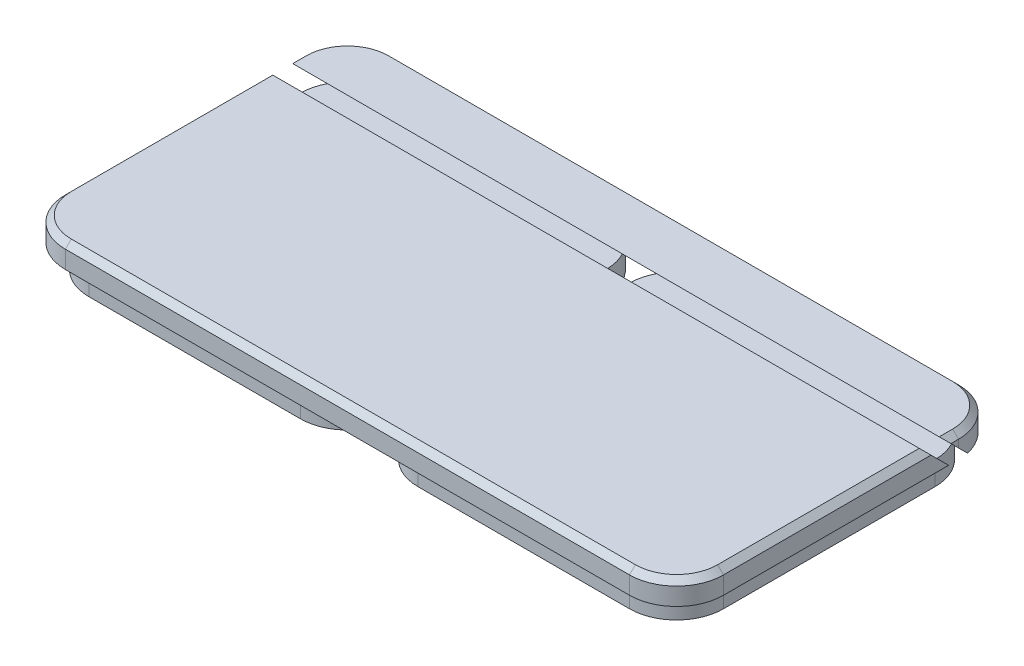
SolidWorks part; units mm, degrees
ref_plane "Front Plane" through (0, 0, 0) normal (0, 0, 1) x (1, 0, 0)
ref_plane "Top Plane" through (0, 0, 0) normal (0, 1, 0) x (1, 0, 0)
ref_plane "Right Plane" through (0, 0, 0) normal (1, 0, 0) x (0, 0, -1)
sketch "Sketch5" plane through (0, 0, 0) normal (0, 1, 0) x (1, 0, 0)
  line L1 (-22.5, -32.5) -> (22.5, -32.5)
  line L2 (-32.5, -22.5) -> (-32.5, 22.5)
  line L3 (-22.5, 32.5) -> (22.5, 32.5)
  line L4 (32.5, -22.5) -> (32.5, 22.5)
  line L5 (-32.5, -32.5) -> (32.5, 32.5) construction
  line L6 (-32.5, 32.5) -> (32.5, -32.5) construction
  arc A0 (-22.5, -32.5) -> (-32.5, -22.5) centre (-22.5, -22.5) cw
  arc A1 (22.5, -32.5) -> (32.5, -22.5) centre (22.5, -22.5) ccw
  arc A2 (22.5, 32.5) -> (32.5, 22.5) centre (22.5, 22.5) cw
  arc A3 (-32.5, 22.5) -> (-22.5, 32.5) centre (-22.5, 22.5) cw
  point P0 (0, 0)
  dimension "D3" = 10
  dimension "D1" = 65
  dimension "D2" = 65
extrude "Boss-Extrude4" add sketch "Sketch5" along normal blind 5
sketch "Sketch6" plane through (0, 5, 0) normal (0, 1, 0) x (1, 0, 0)
  line L1 (35, 35) -> (-35, 35)
  line L2 (35, 35) -> (35, -35)
  line L3 (35, -35) -> (-35, -35)
  line L4 (-35, 35) -> (-35, -35)
  line L5 (35, 35) -> (-35, -35) construction
  line L6 (35, -35) -> (-35, 35) construction
  point P0 (0, 0)
extrude "Boss-Extrude5" add sketch "Sketch6" along normal blind 5
sketch "Sketch8" plane through (0, 0, 0) normal (0, -1, 0) x (1, 0, 0)
  line L0 (-29.5711, 29.5711) -> (-22.5, 22.5)
  arc A0 (-22.5, 32.5) -> (-32.5, 22.5) centre (-22.5, 22.5) ccw construction
  circle A1 centre (-26.0355, 26.0355) radius 3
  circle A2 centre (26.0365, 26.0365) radius 3
  circle A3 centre (26.0375, -26.0355) radius 3
  circle A4 centre (-26.0345, -26.0365) radius 3
  point P8 (0, 0)
  point P15 (0.001, 0.001)
  point P18 (0.002, 0)
  point P21 (0.001, -0.001)
  point P22 (0.001, 0)
  dimension "D1" = 4
extrude "Cut-Extrude1" cut sketch "Sketch8" against normal blind 2 contours A3 | A2 | L0 A1 | L0 A1 | A4
mirror "Mirror1" about plane through (-35, 10, -35) normal (1, 0, 0) of bodies 112
fillet "Fillet1" radius 10 4 edges at (-105, 7.5, 35) (-105, 7.5, -35) (35, 7.5, 35) (35, 7.5, -35)
sketch "Sketch9" plane through (35, 0, 0) normal (1, 0, 0) x (0, 0, -1)
  line L0 (17.8787, 10) -> (22.1213, 10)
  line L1 (-25, 10) -> (25, 10) construction
  line L2 (26.0607, 6.0607) -> (22.1213, 10)
  line L3 (22.8787, 5) -> (18.9393, 8.9393)
  line L4 (18.9393, 8.9393) -> (17.8787, 10)
  line L5 (26.0607, 6.0607) -> (27.1213, 5)
  line L6 (22.5, 5) -> (32.5, 5) construction
  line L7 (27.1213, 5) -> (22.8787, 5)
  line L8 (-25, 5) -> (25, 5) construction
extrude "Cut-Extrude2" cut sketch "Sketch9" against normal through all
chamfer "Chamfer1" distance 1.25 angle 45 10 edges at (35, 10, -23.5607) (-105, 10, -23.5607) (32.0711, 10, -32.0711) (-102.0711, 10, -32.0711) (-35, 10, -35) (-105, 10, 3.5607) (-102.0711, 10, 32.0711) (-35, 10, 35) (32.0711, 10, 32.0711) (35, 10, 3.5607)
